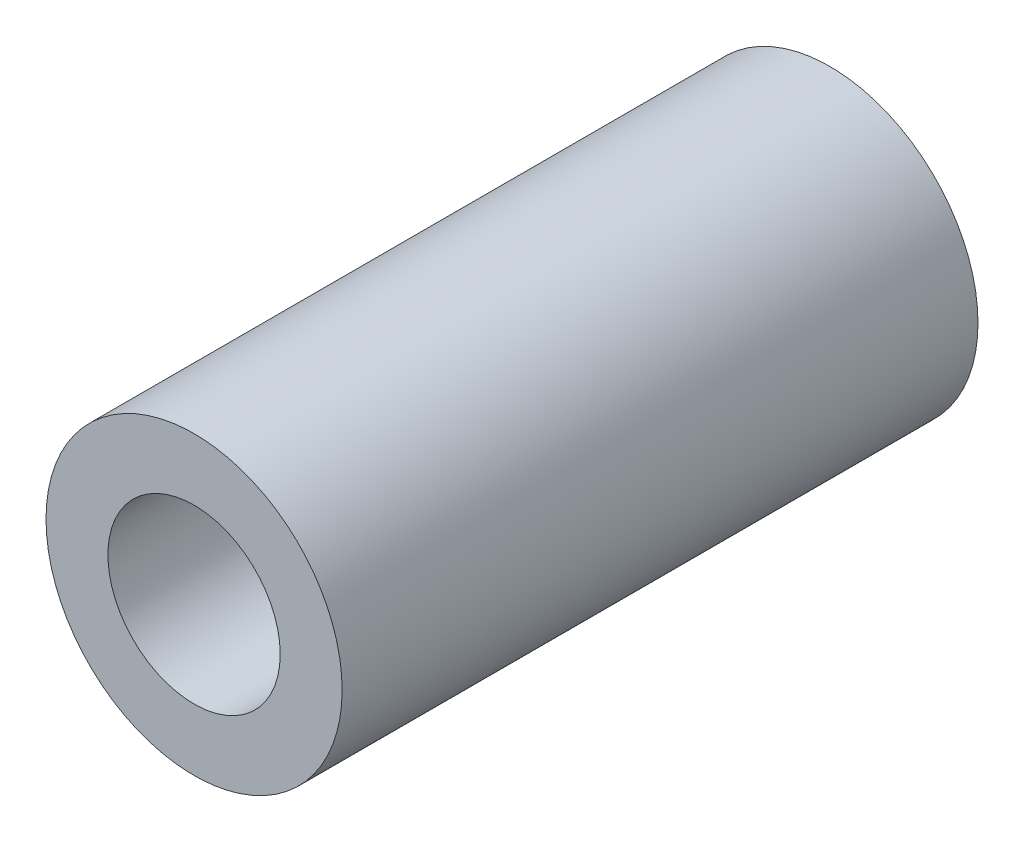
SolidWorks part; units mm, degrees
ref_plane "Front Plane" through (0, 0, 0) normal (0, 0, 1) x (1, 0, 0)
ref_plane "Top Plane" through (0, 0, 0) normal (0, 1, 0) x (1, 0, 0)
ref_plane "Right Plane" through (0, 0, 0) normal (1, 0, 0) x (0, 0, -1)
sketch "草圖1" plane through (0, 0, 0) normal (0, 0, 1) x (1, 0, 0)
  circle A0 centre (0, 0) radius 2.75
  circle A1 centre (0, 0) radius 1.6
extrude "填料-伸長1" add sketch "草圖1" along normal blind 11.81
